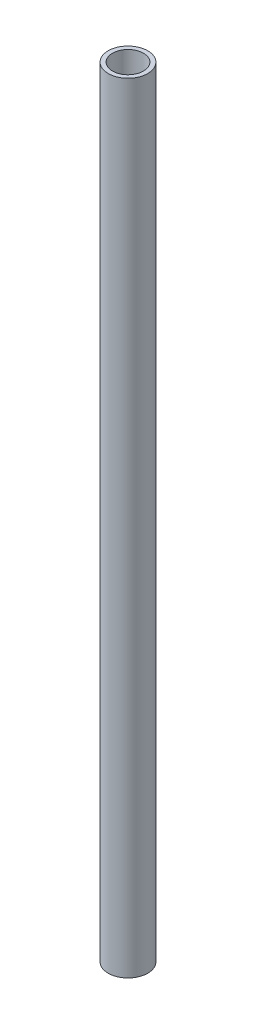
SolidWorks part; units mm, degrees
ref_plane "Front Plane" through (0, 0, 0) normal (0, 0, 1) x (1, 0, 0)
ref_plane "Top Plane" through (0, 0, 0) normal (0, 1, 0) x (1, 0, 0)
ref_plane "Right Plane" through (0, 0, 0) normal (1, 0, 0) x (0, 0, -1)
sketch "Sketch1" plane through (0, 0, 0) normal (0, 0, 1) x (1, 0, 0)
  line L0 (0, 0) -> (0, 420)
  dimension "D1" = 420
other "Pipe - configured 21.3 X 2.3(1)"
ref_plane "Plane1" through (0, 0, 0) normal (0, 1, 0) x (-1, 0, 0)
sketch "Sketch12" plane through (0, 0, 0) normal (0, 1, 0) x (-1, 0, 0)
  circle A0 centre (0, 0) radius 8.35
  circle A1 centre (0, 0) radius 10.65
  point P3 (0, 10.65)
  point P5 (-10.65, 0)
  point P6 (0, -10.65)
  point P7 (10.65, 0)
  point P8 (0, 0)
  dimension "In_dia" = 16.7
  dimension "Out_dia" = 21.3
